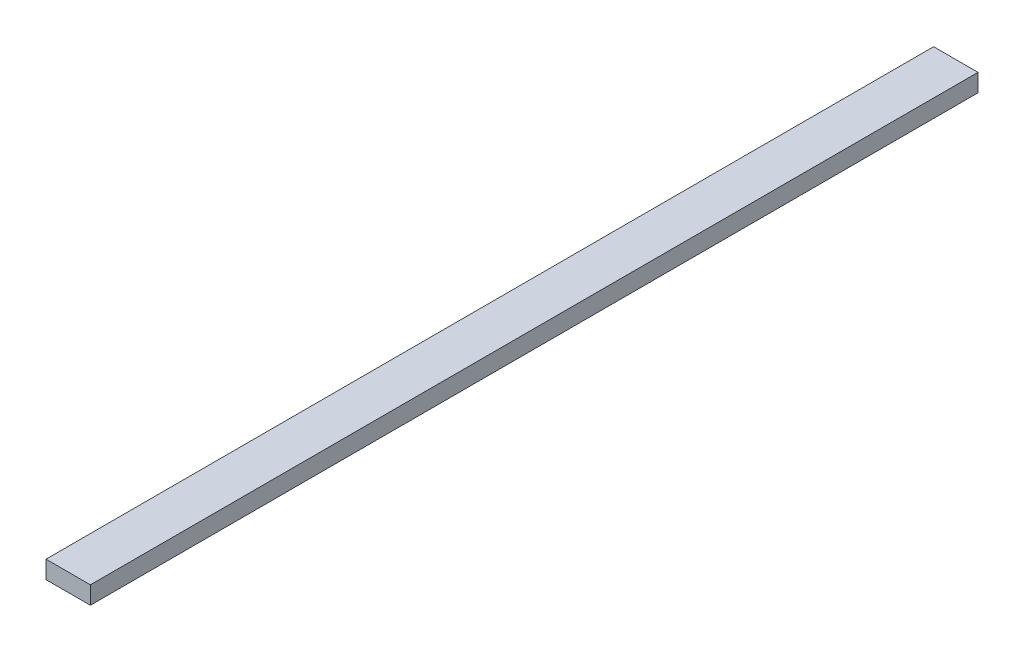
SolidWorks part; units mm, degrees
material "ABS PC"
ref_plane "Alzado" through (0, 0, 0) normal (0, 0, 1) x (1, 0, 0)
ref_plane "Planta" through (0, 0, 0) normal (0, 1, 0) x (1, 0, 0)
ref_plane "Vista lateral" through (0, 0, 0) normal (1, 0, 0) x (0, 0, -1)
sketch "Croquis1" plane through (0, 0, 0) normal (1, 0, 0) x (0, 0, -1)
  line L0 (-110, 24.5) -> (-110, 15) construction
  line L1 (125, -2.5) -> (-125, -2.5)
  line L2 (125, -2.5) -> (125, 2.5)
  line L3 (125, 2.5) -> (-97, 2.5)
  line L4 (-125, -2.5) -> (-125, 2.5)
  line L5 (125, -2.5) -> (0, 0) construction
  line L6 (125, 2.5) -> (-125, -2.5) construction
  line L7 (-117, 17.5) -> (-123, 2.5)
  line L8 (-103, 17.5) -> (-97, 2.5)
  line L9 (-123, 2.5) -> (-125, 2.5)
  circle A0 centre (-110, 17.5) radius 2.5
  arc A1 (-103, 17.5) -> (-117, 17.5) centre (-110, 17.5) ccw
  point P0 (0, 0)
  dimension "D1" = 250
  dimension "D3" = 5
  dimension "D4" = 14
  dimension "D2" = 5
  dimension "D5" = 15
  dimension "D6" = 15
  dimension "D7" = 2
extrude "Saliente-Extruir1" add sketch "Croquis1" along normal mid plane 2.5
sketch "Croquis5" plane through (1.25, 0, 0) normal (1, 0, 0) x (0, 0, -1)
  line L5 (-117, 17.5) -> (-123, 2.5)
  line L6 (-123, 2.5) -> (-125, 2.5)
  line L7 (-125, -2.5) -> (125, -2.5)
  line L8 (125, -2.5) -> (125, 2.5)
  line L9 (-97, 2.5) -> (-103, 17.5)
  line L10 (-117, 17.5) -> (-123, 2.5)
  line L12 (-125, -2.5) -> (125, -2.5)
  line L14 (-97, 2.5) -> (-103, 17.5)
  line L16 (-123, 2.5) -> (-125, 2.5)
  line L17 (-125, 2.5) -> (-125, -2.5)
  line L18 (-125, 2.5) -> (-125, -2.5)
  line L20 (125, -2.5) -> (125, 2.5)
  line L21 (125, 2.5) -> (-97, 2.5)
  line L22 (125, 2.5) -> (-97, 2.5)
  circle A0 centre (-110, 17.5) radius 12.5
  arc A1 (-103, 17.5) -> (-117, 17.5) centre (-110, 17.5) ccw
  arc A2 (-103, 17.5) -> (-117, 17.5) centre (-110, 17.5) ccw
  circle A3 centre (-110, 17.5) radius 15
  dimension "D2" = 25
  dimension "D3" = 30
  dimension "D1" = 0
extrude "Saliente-Extruir4" add sketch "Croquis5" against normal through all contours L14 A3 L10 A0
sketch "Croquis6" plane through (1.25, 0, 0) normal (1, 0, 0) x (0, 0, -1)
  circle A0 centre (-110, 17.5) radius 12.525
  dimension "D1" = 25.05
extrude "Cortar-Extruir3" cut sketch "Croquis6" against normal blind 10
sketch "Croquis7" plane through (0, 0, -125) normal (0, 0, -1) x (-1, 0, 0)
  line L0 (1.25, 32.8) -> (-1.25, 32.8)
  line L1 (1.25, -2.5) -> (3.75, -2.5)
  line L2 (1.25, -2.5) -> (1.25, 2.5) construction
  line L3 (-1.25, 2.5) -> (1.25, 2.5) construction
  line L4 (1.25, -2.5) -> (1.25, 2.5)
  line L5 (-1.25, 2.5) -> (1.25, 2.5)
  line L6 (1.25, 2.5) -> (1.25, 32.8)
  line L7 (1.25, 7.3619) -> (1.25, 32.5) construction
  line L9 (-1.25, 32.8) -> (-1.25, 37.8)
  line L10 (-1.25, 37.8) -> (3.75, 37.8)
  line L11 (3.75, 37.8) -> (3.75, -2.5)
  line M2 (1.25, -2.5) -> (1.25, 2.5)
  dimension "D1" = 30.3
  dimension "D2" = 5
  dimension "D3" = 2.5
extrude "Saliente-Extruir5" add sketch "Croquis7" against normal blind 200 contours L11 L10 L9 L0 L6 L1 M2
sketch "Croquis8" plane through (-1.25, 0, 0) normal (-1, 0, 0) x (0, 0, 1)
  line L0 (97, 2.5) -> (95, 2.5)
  line L1 (75, 2.5) -> (97, 2.5) construction
  line L2 (95, 2.5) -> (95, -2.5)
  line L3 (125, -2.5) -> (75, -2.5) construction
  line L11 (75, 2.5) -> (75, -2.5)
  line L12 (75, -2.5) -> (125, -2.5)
  line L13 (125, -2.5) -> (125, 2.5)
  line L14 (125, 2.5) -> (123, 2.5)
  line L15 (123, 2.5) -> (121.0552, 7.3619)
  line L16 (98.9448, 7.3619) -> (97, 2.5)
  line L17 (97, 2.5) -> (75, 2.5)
  line L18 (75, 2.5) -> (75, -2.5)
  line L19 (75, -2.5) -> (125, -2.5)
  line L20 (125, -2.5) -> (125, 2.5)
  line L21 (125, 2.5) -> (123, 2.5)
  line L22 (123, 2.5) -> (121.0552, 7.3619)
  line L23 (98.9448, 7.3619) -> (97, 2.5)
  line L24 (97, 2.5) -> (75, 2.5)
  circle A0 centre (110, 17.5) radius 12.525 construction
  arc A1 (121.0552, 7.3619) -> (98.9448, 7.3619) centre (110, 17.5) ccw
  arc A2 (121.0552, 7.3619) -> (98.9448, 7.3619) centre (110, 17.5) ccw
  circle A3 centre (110, 17.5) radius 12.525
  circle M2 centre (110, 17.5) radius 12.525
  line M4 (75, -2.5) -> (125, -2.5)
  line M5 (125, -2.5) -> (125, 2.5)
  line M6 (125, 2.5) -> (123, 2.5)
  line M7 (123, 2.5) -> (121.0552, 7.3619)
  arc M8 (121.0552, 7.3619) -> (98.9448, 7.3619) centre (110, 17.5) ccw
  line M9 (98.9448, 7.3619) -> (97, 2.5)
  line M10 (97, 2.5) -> (75, 2.5)
  dimension "D1" = 2
  dimension "D2" = 0
extrude "Saliente-Extruir6" add sketch "Croquis8" along normal blind 21 contours L2 M10 M4 M5 M6 M7 M8 M9 M2
sketch "Croquis10" plane through (0, 0, 75) normal (0, 0, 1) x (1, 0, 0)
  line L0 (1.25, 2.5) -> (1.25, 7.3619) construction
  line L1 (-22.25, 7.3619) -> (-22.25, 2.5) construction
  line L2 (-22.25, 2.5) -> (1.25, 2.5) construction
  line L3 (1.25, 2.5) -> (-22.25, 2.5) construction
  line L4 (-22.25, 2.5) -> (-22.25, -2.5) construction
  line L5 (-22.25, -2.5) -> (1.25, -2.5) construction
  line L6 (1.25, -2.5) -> (1.25, 2.5) construction
  line L7 (-3.75, 37.8) -> (-3.75, -2.5)
  line L8 (-3.75, -2.5) -> (-1.25, -2.5)
  line L9 (-1.25, -2.5) -> (-1.25, 2.5)
  line L10 (-1.25, 2.5) -> (-1.25, 32.8)
  line L11 (-1.25, 32.8) -> (1.25, 32.8)
  line L12 (1.25, 32.8) -> (1.25, 37.8)
  line L13 (1.25, 37.8) -> (-3.75, 37.8)
  line L14 (-3.75, 37.8) -> (-3.75, -2.5)
  line L15 (-3.75, -2.5) -> (-1.25, -2.5)
  line L16 (-1.25, -2.5) -> (-1.25, 2.5)
  line L17 (-1.25, 2.5) -> (-1.25, 32.8)
  line L18 (-1.25, 32.8) -> (1.25, 32.8)
  line L19 (1.25, 32.8) -> (1.25, 37.8)
  line L20 (1.25, 37.8) -> (-3.75, 37.8)
  line L21 (1.25, 7.3619) -> (1.25, 32.5) construction
  line L22 (1.25, 7.3619) -> (-22.25, 7.3619) construction
  line L23 (-22.25, 32.5) -> (-22.25, 7.3619) construction
  line L24 (1.25, 2.5) -> (1.25, 7.3619)
  line L25 (-22.25, 7.3619) -> (-22.25, 2.5)
  line L26 (-22.25, 2.5) -> (1.25, 2.5)
  line L27 (1.25, 2.5) -> (-22.25, 2.5)
  line L28 (-22.25, 2.5) -> (-22.25, -2.5)
  line L29 (-22.25, -2.5) -> (1.25, -2.5)
  line L30 (1.25, -2.5) -> (1.25, 2.5)
  line L31 (1.25, 7.3619) -> (1.25, 32.5)
  line L32 (1.25, 7.3619) -> (-22.25, 7.3619)
  line L33 (-22.25, 32.5) -> (-22.25, 7.3619)
  line L38 (-22.25, 32.5) -> (1.25, 32.5)
  line M8 (-3.75, 37.8) -> (-3.75, -2.5)
  line M9 (-3.75, -2.5) -> (-1.25, -2.5)
  line M10 (-1.25, -2.5) -> (-1.25, 2.5)
  line M11 (-1.25, 2.5) -> (-1.25, 32.8)
  line M12 (-1.25, 32.8) -> (1.25, 32.8)
  line M13 (1.25, 32.8) -> (1.25, 37.8)
  line M14 (1.25, 37.8) -> (-3.75, 37.8)
  dimension "D1" = 0
extrude "Cortar-Extruir5" cut sketch "Croquis10" along normal blind 98 contours L38 L33 L32 L14 | L38 M8 M11 M12 M13 M14 | L38 L17 L32 L31 | L38 L14 L32 L17 | L14 L32 L25 L26 | L32 L14 L26 M11 | L24 L32 L26 M11 | L26 L14 M9 M10 | L28 L29 L14 L26 | L29 L30 L26 M10
sketch "Croquis11" plane through (0, 0, 75) normal (0, 0, 1) x (1, 0, 0)
  line L8 (-3.75, 37.8) -> (-3.75, -2.5)
  line L9 (-3.75, -2.5) -> (1.25, -2.5)
  line L10 (1.25, -2.5) -> (1.25, 2.5)
  line L11 (1.25, 2.5) -> (-1.25, 2.5)
  line L12 (-1.25, 2.5) -> (-1.25, 32.8)
  line L13 (-1.25, 32.8) -> (1.25, 32.8)
  line L14 (1.25, 32.8) -> (1.25, 37.8)
  line L15 (1.25, 37.8) -> (-3.75, 37.8)
  line L16 (-3.75, 37.8) -> (-3.75, -2.5)
  line L17 (-3.75, -2.5) -> (1.25, -2.5)
  line L18 (1.25, -2.5) -> (1.25, 2.5)
  line L19 (1.25, 2.5) -> (-1.25, 2.5)
  line L20 (-1.25, 2.5) -> (-1.25, 32.8)
  line L21 (-1.25, 32.8) -> (1.25, 32.8)
  line L22 (1.25, 32.8) -> (1.25, 37.8)
  line L23 (1.25, 37.8) -> (-3.75, 37.8)
  dimension "D1" = 0
extrude "Saliente-Extruir7" add sketch "Croquis11" along normal blind 50
sketch "Croquis14" plane through (0, 0, 125) normal (0, 0, 1) x (1, 0, 0)
  line L0 (-1.25, 32.8) -> (1.25, 32.8) construction
  line L1 (1.25, 37.8) -> (-3.75, 37.8) construction
  line L2 (1.25, 32.8) -> (1.25, 37.8) construction
  line L3 (-1.25, 32.8) -> (1.25, 32.8)
  line L4 (1.25, 37.8) -> (-3.75, 37.8)
  line L5 (1.25, 32.8) -> (1.25, 37.8)
  line L6 (-1.25, 32.8) -> (-3.75, 32.8)
  line L7 (-3.75, 37.8) -> (-3.75, 32.8)
  line L8 (-3.75, 37.8) -> (-3.75, -2.5) construction
extrude "Saliente-Extruir8" add sketch "Croquis14" along normal blind 15 and the other way blind 265
sketch "Croquis15" plane through (1.25, 0, 0) normal (1, 0, 0) x (0, 0, -1)
  line L0 (125, 2.5) -> (-125, 2.5) construction
  line L1 (-125, 2.5) -> (-125, -2.5) construction
  line L2 (-125, -2.5) -> (125, -2.5) construction
  line L3 (125, -2.5) -> (125, 2.5) construction
  line L4 (-140, 32.8) -> (140, 32.8) construction
  line L5 (140, 32.8) -> (140, 37.8) construction
  line L6 (140, 37.8) -> (-140, 37.8) construction
  line L7 (-140, 37.8) -> (-140, 32.8) construction
  line L8 (125, 2.5) -> (-125, 2.5)
  line L9 (-125, 2.5) -> (-125, -2.5)
  line L10 (-125, -2.5) -> (125, -2.5)
  line L11 (125, -2.5) -> (125, 2.5)
  line L12 (-140, 32.8) -> (140, 32.8)
  line L13 (140, 32.8) -> (140, 37.8)
  line L14 (140, 37.8) -> (-140, 37.8)
  line L15 (-140, 37.8) -> (-140, 32.8)
extrude "Saliente-Extruir9" add sketch "Croquis15" along normal blind 7.5
sketch "Croquis16" plane through (-1.25, 0, 0) normal (1, 0, 0) x (0, 0, -1)
  line L0 (-140, 37.8) -> (-140, 32.8) construction
  line L1 (-140, 32.8) -> (140, 32.8) construction
  line L2 (140, 32.8) -> (140, 37.8) construction
  line L3 (140, 37.8) -> (-140, 37.8) construction
  line L4 (125, 32.8) -> (-125, 32.8) construction
  line L5 (-125, 32.8) -> (-125, 2.5) construction
  line L6 (-125, 2.5) -> (125, 2.5) construction
  line L7 (125, 2.5) -> (125, 32.8) construction
  line L8 (-140, 37.8) -> (-140, 32.8)
  line L9 (-140, 32.8) -> (140, 32.8)
  line L10 (140, 32.8) -> (140, 37.8)
  line L11 (140, 37.8) -> (-140, 37.8)
  line L12 (125, 32.8) -> (-125, 32.8)
  line L13 (-125, 32.8) -> (-125, 2.5)
  line L14 (-125, 2.5) -> (125, 2.5)
  line L15 (125, 2.5) -> (125, 32.8)
extrude "Cortar-Extruir6" cut sketch "Croquis16" against normal blind 86 contours L12 L13 L14 L15 | L8 L9 L10 L11
delete or keep bodies "Sólido-Eliminar/Conservar 1" type delete bodies bodies 120
